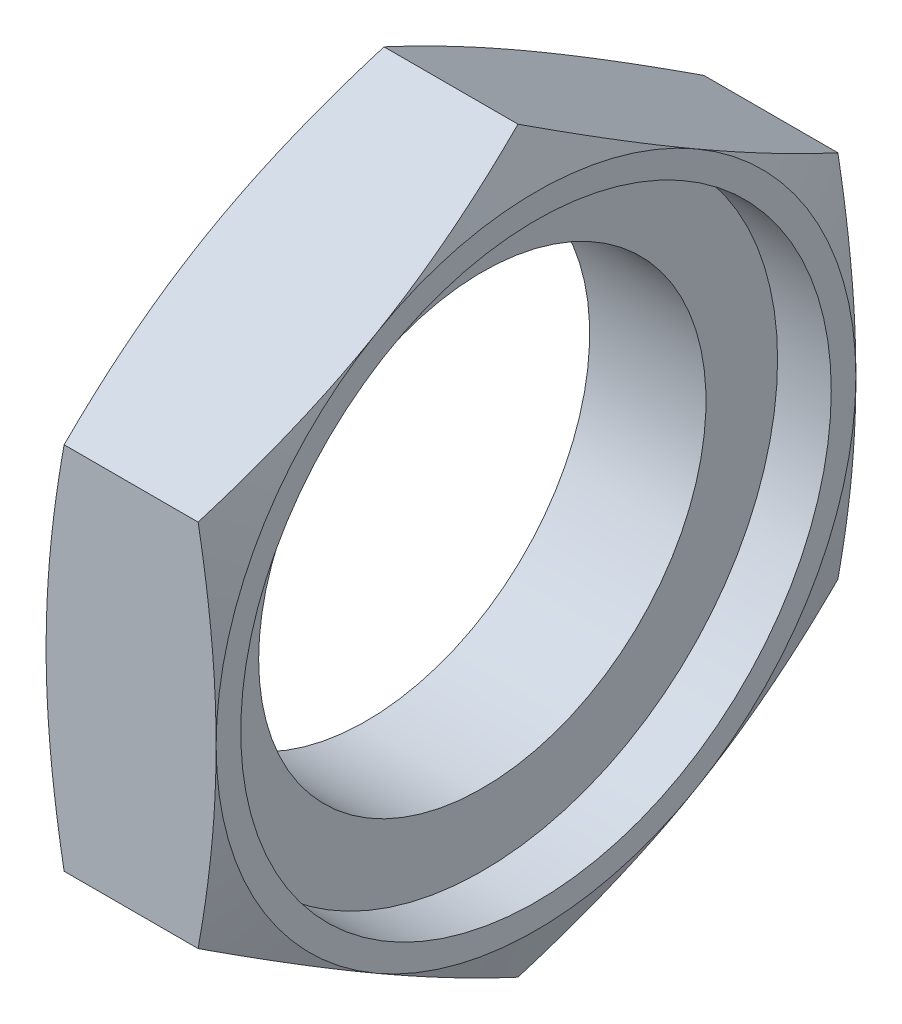
SolidWorks part; units mm, degrees
material "AISI 1020"
ref_plane "Plano superior" through (0, 0, 0) normal (0, 0, 1) x (1, 0, 0)
ref_plane "Plano frontal" through (0, 0, 0) normal (0, 1, 0) x (1, 0, 0)
ref_plane "Plano direito" through (0, 0, 0) normal (1, 0, 0) x (0, 0, -1)
sketch "Esboço1" plane through (0, 0, 0) normal (1, 0, 0) x (0, 0, -1)
  line L0 (0, 0) -> (0, 19.1524) construction
  line L1 (14.3, 8.2561) -> (0, 16.5122)
  line L2 (0, 16.5122) -> (-14.3, 8.2561)
  line L3 (-14.3, 8.2561) -> (-14.3, -8.2561)
  line L4 (-14.3, -8.2561) -> (0, -16.5122)
  line L5 (0, -16.5122) -> (14.3, -8.2561)
  line L6 (14.3, -8.2561) -> (14.3, 8.2561)
  circle A0 centre (0, 0) radius 14.3 construction
  circle A1 centre (0, 0) radius 10
  dimension "D1" = 28.6
  dimension "D2" = 20
extrude "Ressalto-extrusão1" add sketch "Esboço1" along normal blind 7.6
cosmetic thread "Representação de rosca2" parameters "D2"=22
sketch "Esboço3" plane through (0, 0, 0) normal (-1, 0, 0) x (0, 0, 1)
  circle A0 centre (0, 0) radius 14.3
sketch "Esboço4" plane through (7.6, 0, 0) normal (1, 0, 0) x (0, 0, -1)
  circle A0 centre (0, 0) radius 14.3
hole_wizard "Furo1" positions "Esboço5" profile "Esboço6" legacy
sketch "Esboço5" plane through (7.6, 0, 0) normal (1, 0, 0) x (0, 0, -1)
  point P0 (0, 0)
  point P3 (0, 0)
sketch "Esboço6" plane through (7.6, 0, 0) normal (0, 1, 0) x (0, 0, -1)
  line L0 (0, 0) -> (0, 2.4)
  line L1 (0, 2.4) -> (13.2, 2.4)
  line L2 (13.2, 2.4) -> (13.2, 0)
  line L3 (13.2, 0) -> (0, 0)
  line L4 (0, 110) -> (0, -10) construction
  dimension "Diameter" = 26.4
  dimension "Depth" = 2.4
sketch "Esboço7" plane through (7.6, 0, 0) normal (1, 0, 0) x (0, 0, -1)
  circle A0 centre (0, 0) radius 14.3
extrude "Corte-extrusão1" cut sketch "Esboço7" against normal blind 13 draft 70 flip side to cut
sketch "Esboço8" plane through (0, 0, 0) normal (-1, 0, 0) x (0, 0, 1)
  circle A0 centre (0, 0) radius 14.3
extrude "Corte-extrusão2" cut sketch "Esboço8" against normal blind 13 draft 70 flip side to cut
